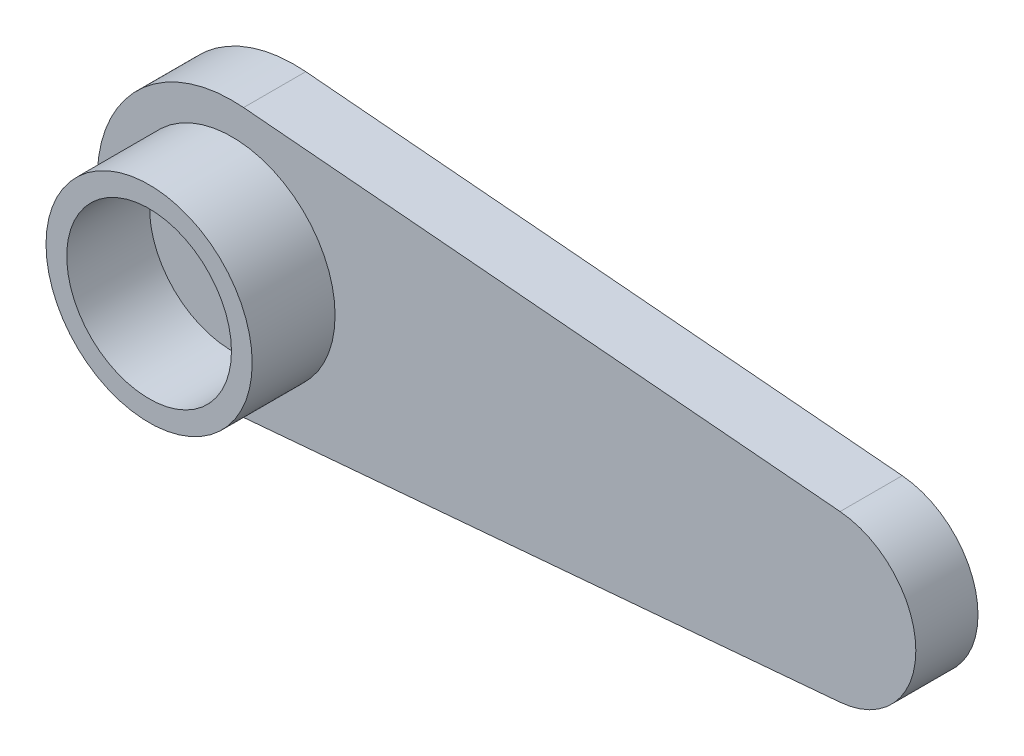
SolidWorks part; units mm, degrees
ref_plane "Front Plane" through (0, 0, 0) normal (0, 0, 1) x (1, 0, 0)
ref_plane "Top Plane" through (0, 0, 0) normal (0, 1, 0) x (1, 0, 0)
ref_plane "Right Plane" through (0, 0, 0) normal (1, 0, 0) x (0, 0, -1)
sketch "Sketch1" plane through (0, 0, 0) normal (0, 0, 1) x (1, 0, 0)
  line L0 (-28.6203, 6.4758) -> (0.1642, 3.9851)
  line L1 (-44.2447, 0) -> (44.2447, 0) construction
  line L2 (-28.6203, -6.4758) -> (0.1642, -3.9851)
  arc A0 (-28.6203, 6.4758) -> (-28.6203, -6.4758) centre (-29.1806, 0) ccw
  arc A1 (0.1642, -3.9851) -> (0.1642, 3.9851) centre (-0.1806, 0) ccw
extrude "Boss-Extrude1" add sketch "Sketch1" along normal blind 3
sketch "Sketch2" plane through (0, 0, 3) normal (0, 0, 1) x (1, 0, 0)
  circle A0 centre (-29.1806, 0) radius 4.975
  dimension "D1" = 9.95
extrude "Extrude-Thin1" add sketch "Sketch2" along normal blind 4 thin thin type one direction reverse wall 1
sketch "Sketch3" plane through (0, 0, 0) normal (0, 0, -1) x (-1, 0, 0)
  line L0 (29.1806, -4.2156) -> (29.1806, 4.2156) construction
  line L1 (25.4279, 0) -> (32.9333, 0) construction
  line L2 (28.9369, 2.6388) -> (29.1806, 3.1352)
  circle A0 centre (29.1806, 0) radius 2.65
  point P6 (29.1806, 0)
  point P10 (29.1806, 0)
  dimension "D1" = 5.3
